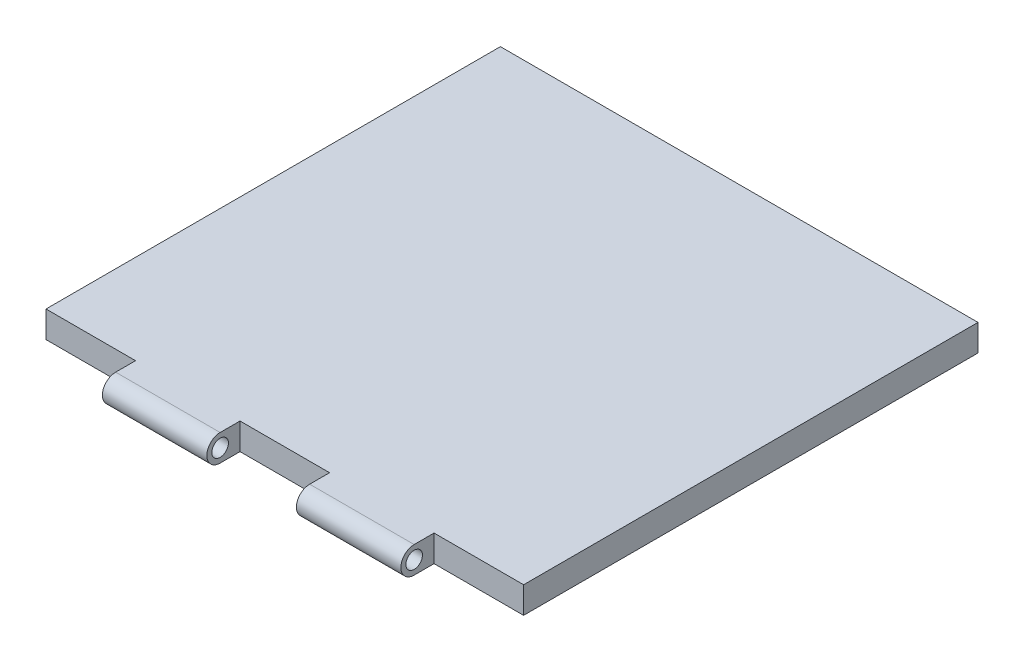
SolidWorks part; units mm, degrees
ref_plane "Front Plane" through (0, 0, 0) normal (0, 0, 1) x (1, 0, 0)
ref_plane "Top Plane" through (0, 0, 0) normal (0, 1, 0) x (1, 0, 0)
ref_plane "Right Plane" through (0, 0, 0) normal (1, 0, 0) x (0, 0, -1)
sketch "Sketch3" plane through (0, 0, 0) normal (1, 0, 0) x (0, 0, -1)
  line L0 (-35.75, 2.8574) -> (35.75, 2.8574)
  line L1 (35.75, 2.8574) -> (35.75, -1.1426)
  line L2 (35.75, -1.1426) -> (-35.75, -1.1426)
  circle A1 centre (-35.75, 0.8574) radius 1.25
  arc A2 (-35.75, -1.1426) -> (-35.75, 2.8574) centre (-35.75, 0.8574) cw
  point P6 (0, 0)
  point P7 (0, 2.8574)
  point P10 (-37.75, 0.8574)
  dimension "D3" = 2.5
  dimension "D2" = 4
  dimension "D4" = 73.5
extrude "Boss-Extrude2" add sketch "Sketch3" along normal mid plane 72
sketch "Sketch4" plane through (0, 0, 0) normal (0, 1, 0) x (1, 0, 0)
  line L0 (-36, -37.75) -> (36, -37.75) construction
  line L1 (-36, -32.75) -> (-22.5, -32.75)
  line L2 (-36, -32.75) -> (-36, -37.75)
  line L3 (-36, -37.75) -> (-22.5, -37.75)
  line L4 (-22.5, -32.75) -> (-22.5, -37.75)
  line L5 (36, -35.75) -> (-36, -35.75) construction
  line L6 (36, -32.75) -> (22.5, -32.75)
  line L7 (36, -32.75) -> (36, -37.75)
  line L8 (36, -37.75) -> (22.5, -37.75)
  line L9 (22.5, -32.75) -> (22.5, -37.75)
  line L10 (0, -35.75) -> (0, -15.1444) construction
  line L11 (-36, 35.75) -> (-36, -35.75) construction
  line L12 (-6.75, -32.75) -> (6.75, -32.75)
  line L13 (-6.75, -32.75) -> (-6.75, -37.75)
  line L14 (-6.75, -37.75) -> (6.75, -37.75)
  line L15 (6.75, -32.75) -> (6.75, -37.75)
  line L16 (36, 35.75) -> (36, -35.75) construction
  point P20 (0, -32.75)
  dimension "D1" = 13.5
  dimension "D2" = 13.5
  dimension "D3" = 13.5
  dimension "D4" = 5
extrude "Cut-Extrude1" cut sketch "Sketch4" against normal through all both and the other way through all
sketch "Sketch7" plane through (0, 0, 0) normal (1, 0, 0) x (0, 0, -1)
  line L4 (30.8763, -1.1426) -> (30.8763, -3.8787)
  line L5 (-32.75, -1.1426) -> (35.75, -1.1426) construction
  line L6 (30.8763, -3.8787) -> (19.8083, -1.1426)
  line L7 (19.8083, -1.1426) -> (30.8763, -1.1426)
extrude "Boss-Extrude3" add sketch "Sketch7" along normal mid plane 60
equation "\"box_width\"=112"
equation "\"wall\"=2.5"
equation "\"box_length\"= 67"
equation "\"openable_top\"= 72"
equation "\"axis_hole\"=2.5"
equation "\"D1@Boss-Extrude2\"=\"box_length\"+\"wall\"*2"
equation "\"given_to_axis\"= 1"
equation "\"to_fit_in_when_closing\"= 1"
